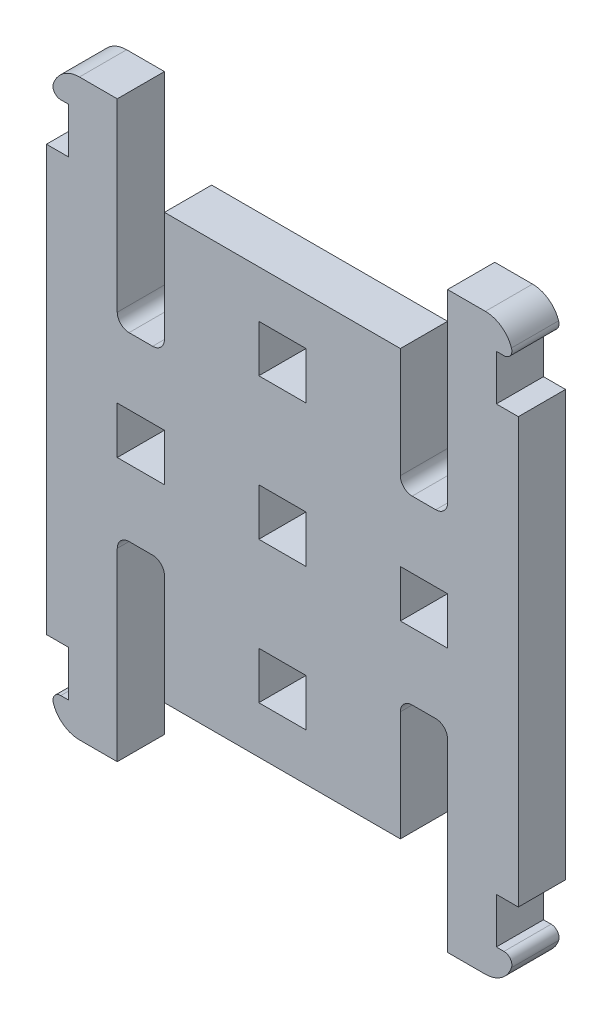
SolidWorks part; units mm, degrees
ref_plane "Alzado" through (0, 0, 0) normal (0, 0, 1) x (1, 0, 0)
ref_plane "Planta" through (0, 0, 0) normal (0, 1, 0) x (1, 0, 0)
ref_plane "Vista lateral" through (0, 0, 0) normal (1, 0, 0) x (0, 0, -1)
sketch "Model" plane through (0, 0, 0) normal (0, 0, 1) x (1, 0, 0)
  line L0 (24.621, 290.4055) -> (24.621, 287.4055)
  line L1 (27.621, 290.4055) -> (24.621, 290.4055)
  line L2 (27.621, 287.4055) -> (27.621, 290.4055)
  line L3 (24.621, 287.4055) -> (27.621, 287.4055)
  line L4 (15.621, 281.4055) -> (15.621, 278.4055)
  line L5 (18.621, 281.4055) -> (15.621, 281.4055)
  line L6 (18.621, 278.4055) -> (18.621, 281.4055)
  line L7 (15.621, 278.4055) -> (18.621, 278.4055)
  line L8 (24.621, 281.4055) -> (24.621, 278.4055)
  line L9 (27.621, 281.4055) -> (24.621, 281.4055)
  line L10 (27.621, 278.4055) -> (27.621, 281.4055)
  line L11 (24.621, 278.4055) -> (27.621, 278.4055)
  line L12 (24.621, 272.4055) -> (24.621, 269.4055)
  line L13 (27.621, 272.4055) -> (24.621, 272.4055)
  line L14 (27.621, 269.4055) -> (27.621, 272.4055)
  line L15 (24.621, 269.4055) -> (27.621, 269.4055)
  line L16 (33.621, 281.4055) -> (33.621, 278.4055)
  line L17 (36.621, 281.4055) -> (33.621, 281.4055)
  line L18 (36.621, 278.4055) -> (36.621, 281.4055)
  line L19 (33.621, 278.4055) -> (36.621, 278.4055)
  line L20 (36.621, 298.1555) -> (39.0239, 298.1555)
  line L21 (40.2082, 296.3055) -> (39.721, 296.3055)
  line L22 (39.721, 293.4055) -> (39.721, 296.3055)
  line L23 (39.721, 293.4055) -> (41.121, 293.4055)
  line L24 (33.621, 293.4055) -> (18.621, 293.4055)
  line L25 (36.621, 261.6555) -> (39.0239, 261.6555)
  line L26 (39.721, 266.4055) -> (39.721, 263.5055)
  line L27 (40.2082, 263.5055) -> (39.721, 263.5055)
  line L28 (39.721, 266.4055) -> (41.121, 266.4055)
  line L29 (33.621, 266.4055) -> (18.621, 266.4055)
  line L30 (35.871, 285.6555) -> (34.371, 285.6555)
  line L31 (33.621, 266.4055) -> (33.621, 273.4055)
  line L32 (36.621, 273.4055) -> (36.621, 261.6555)
  line L33 (16.371, 274.1555) -> (17.871, 274.1555)
  line L34 (36.621, 286.4055) -> (36.621, 298.1555)
  line L35 (33.621, 286.4055) -> (33.621, 293.4055)
  line L36 (41.121, 266.4055) -> (41.121, 293.4055)
  line L37 (15.621, 298.1555) -> (13.2182, 298.1555)
  line L38 (12.0339, 296.3055) -> (12.521, 296.3055)
  line L39 (12.521, 293.4055) -> (11.121, 293.4055)
  line L40 (12.521, 293.4055) -> (12.521, 296.3055)
  line L41 (12.521, 266.4055) -> (11.121, 266.4055)
  line L42 (15.621, 261.6555) -> (13.2182, 261.6555)
  line L43 (12.521, 266.4055) -> (12.521, 263.5055)
  line L44 (12.0339, 263.5055) -> (12.521, 263.5055)
  line L45 (17.871, 285.6555) -> (16.371, 285.6555)
  line L46 (15.621, 261.6555) -> (15.621, 273.4055)
  line L47 (18.621, 273.4055) -> (18.621, 266.4055)
  line L48 (18.621, 286.4055) -> (18.621, 293.4055)
  line L49 (15.621, 286.4055) -> (15.621, 298.1555)
  line L50 (11.121, 266.4055) -> (11.121, 293.4055)
  line L51 (34.371, 274.1555) -> (35.871, 274.1555)
  arc A0 (40.2082, 296.3055) -> (40.6819, 296.9655) centre (40.2082, 296.8055) ccw
  arc A1 (40.6819, 296.9655) -> (39.0239, 298.1555) centre (39.0239, 296.4055) ccw
  arc A2 (40.6819, 262.8455) -> (40.2082, 263.5055) centre (40.2082, 263.0055) ccw
  arc A3 (39.0239, 261.6555) -> (40.6819, 262.8455) centre (39.0239, 263.4055) ccw
  arc A4 (33.621, 286.4055) -> (34.371, 285.6555) centre (34.371, 286.4055) ccw
  arc A5 (35.871, 285.6555) -> (36.621, 286.4055) centre (35.871, 286.4055) ccw
  arc A6 (18.621, 273.4055) -> (17.871, 274.1555) centre (17.871, 273.4055) ccw
  arc A7 (16.371, 274.1555) -> (15.621, 273.4055) centre (16.371, 273.4055) ccw
  arc A8 (11.5602, 296.9655) -> (12.0339, 296.3055) centre (12.0339, 296.8055) ccw
  arc A9 (13.2182, 298.1555) -> (11.5602, 296.9655) centre (13.2182, 296.4055) ccw
  arc A10 (12.0339, 263.5055) -> (11.5602, 262.8455) centre (12.0339, 263.0055) ccw
  arc A11 (11.5602, 262.8455) -> (13.2182, 261.6555) centre (13.2182, 263.4055) ccw
  arc A12 (15.621, 286.4055) -> (16.371, 285.6555) centre (16.371, 286.4055) ccw
  arc A13 (17.871, 285.6555) -> (18.621, 286.4055) centre (17.871, 286.4055) ccw
  arc A14 (36.621, 273.4055) -> (35.871, 274.1555) centre (35.871, 273.4055) ccw
  arc A15 (34.371, 274.1555) -> (33.621, 273.4055) centre (34.371, 273.4055) ccw
extrude "Saliente-Extruir1" add sketch "Model" along normal blind 3
